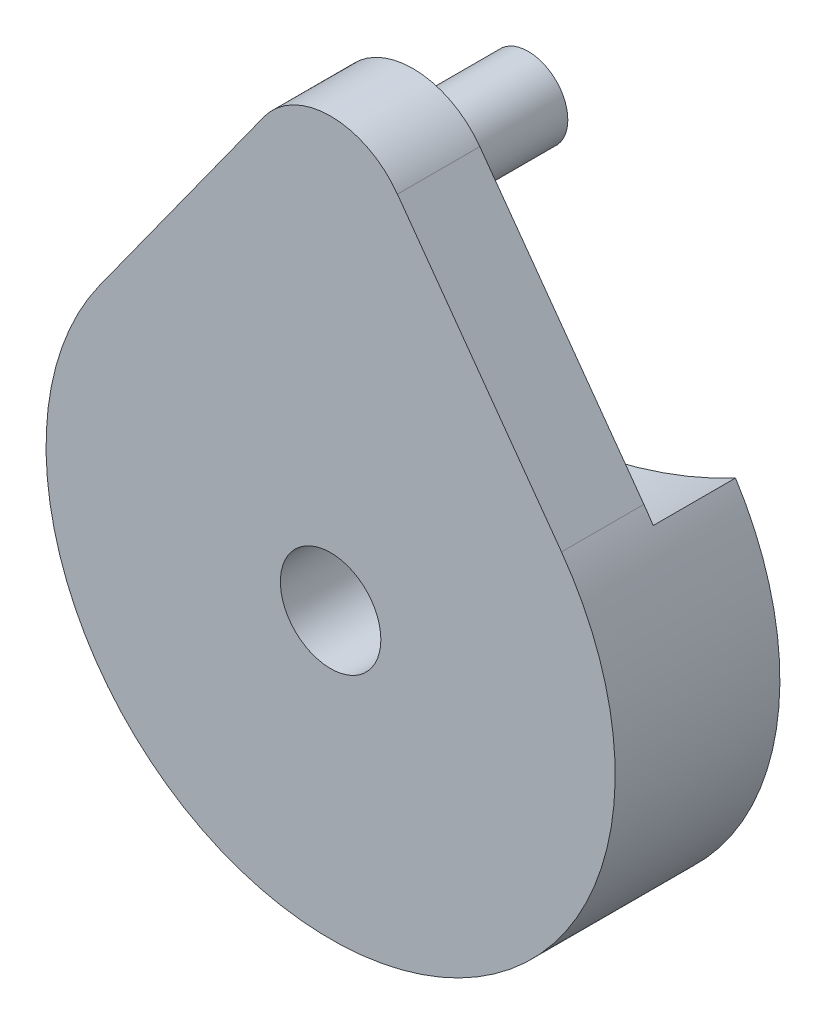
SolidWorks part; units mm, degrees
ref_plane "Front Plane" through (0, 0, 0) normal (0, 0, 1) x (1, 0, 0)
ref_plane "Top Plane" through (0, 0, 0) normal (0, 1, 0) x (1, 0, 0)
ref_plane "Right Plane" through (0, 0, 0) normal (1, 0, 0) x (0, 0, -1)
sketch "Sketch1" plane through (0, 0, 0) normal (0, 0, 1) x (1, 0, 0)
  line L0 (-14.0161, -26.5245) -> (-4.0572, -12.6975)
  line L1 (0, 0) -> (0, -72.2998) construction
  line L2 (14.0161, -26.5245) -> (4.0572, -12.6975)
  line L3 (0, 0) -> (-24.9211, -35.6015) construction
  circle A0 centre (0, 0) radius 30 construction
  circle A1 centre (0, -36.6197) radius 3.05 construction
  arc A2 (4.0572, -12.6975) -> (-4.0572, -12.6975) centre (0, -15.6197) ccw
  arc A3 (-14.0161, -26.5245) -> (14.0161, -26.5245) centre (0, -36.6197) ccw
  circle A4 centre (0, 0) radius 2.5 construction
  circle A5 centre (0, -15.6197) radius 2.5 construction
  circle A6 centre (0, -36.6197) radius 17.2733 construction
  circle A7 centre (0, -36.6197) radius 21 construction
  point P16 (-17.2039, -24.577)
  dimension "D2" = 5
  dimension "D3" = 60
  dimension "D4" = 42
  dimension "D5" = 6.1
  dimension "D6" = 5
  dimension "D7" = 5
extrude "Extrude1" add sketch "Sketch1" along normal mid plane 5
sketch "Sketch2" plane through (0, 0, -2.5) normal (0, 0, -1) x (-1, 0, 0)
  line L0 (0, -36.6197) -> (0, 5.8308) construction
  arc A0 (-14.58, -27.3574) -> (14.58, -27.3574) centre (0, -36.6197) ccw
  circle A1 centre (0, -36.6197) radius 17.2733 construction
  arc A6 (-14.58, -27.3574) -> (14.58, -27.3574) centre (0, 0) ccw
  dimension "D2" = 31
extrude "Extrude2" add sketch "Sketch2" along normal blind 5
sketch "Sketch4" plane through (0, 0, 2.5) normal (0, 0, 1) x (1, 0, 0)
  circle A0 centre (0, -36.6197) radius 3.05
  circle A2 centre (0, -36.6197) radius 3.05 construction
extrude "Extrude4" cut sketch "Sketch4" against normal through all
sketch "Sketch5" plane through (0, 0, -2.5) normal (0, 0, -1) x (-1, 0, 0)
  circle A0 centre (0, -15.6197) radius 2.4
  dimension "D1" = 4.8
extrude "Boss-Extrude1" add sketch "Sketch5" along normal blind 7
equation "\"n\"=10"
